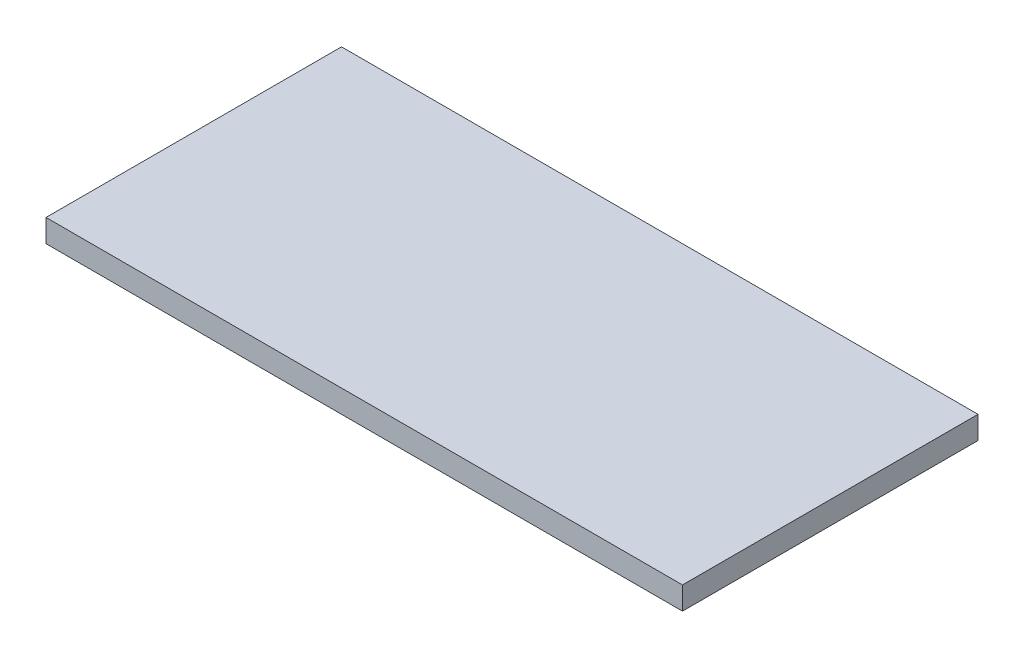
SolidWorks part; units mm, degrees
material "Cedar"
ref_plane "Front Plane" through (0, 0, 0) normal (0, 0, 1) x (1, 0, 0)
ref_plane "Top Plane" through (0, 0, 0) normal (0, 1, 0) x (1, 0, 0)
ref_plane "Right Plane" through (0, 0, 0) normal (1, 0, 0) x (0, 0, -1)
sketch "Sketch1" plane through (0, 0, 0) normal (0, 1, 0) x (1, 0, 0)
  line L0 (-140, 65) -> (140, -65) construction
  line L1 (-140, -65) -> (140, -65)
  line L2 (-140, -65) -> (-140, 65)
  line L3 (-140, 65) -> (140, 65)
  line L4 (140, -65) -> (140, 65)
  line L5 (140, 65) -> (-140, -65) construction
  point P4 (0, 0)
  dimension "D1" = 280
  dimension "D2" = 130
extrude "Boss-Extrude1" add sketch "Sketch1" along normal blind 10
